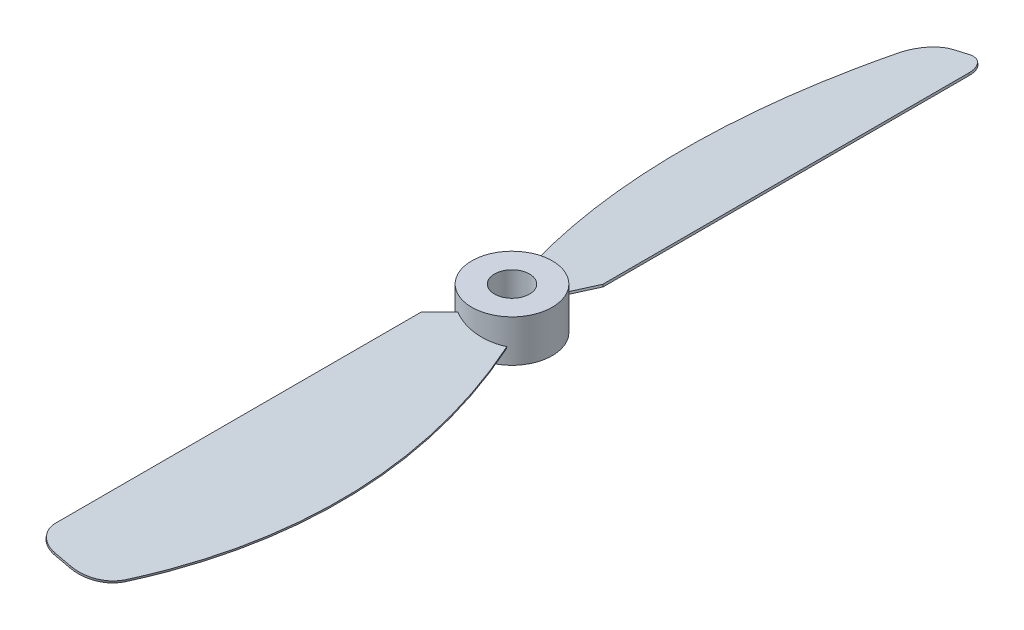
SolidWorks part; units mm, degrees
ref_plane "Front Plane" through (0, 0, 0) normal (0, 0, 1) x (1, 0, 0)
ref_plane "Top Plane" through (0, 0, 0) normal (0, 1, 0) x (1, 0, 0)
ref_plane "Right Plane" through (0, 0, 0) normal (1, 0, 0) x (0, 0, -1)
sketch "Sketch1" plane through (0, 0, 0) normal (0, 1, 0) x (1, 0, 0)
  circle A0 centre (0, 0) radius 5.75
  dimension "D1" = 11.5
extrude "Boss-Extrude1" add sketch "Sketch1" along normal mid plane 6
sketch "Sketch3" plane through (0, 0, 0) normal (0, 0, 1) x (1, 0, 0)
  line L0 (-5.75, 1.3275) -> (5.75, -1.3275) construction
  line L1 (5.75, -3) -> (5.75, 3) construction
  line L2 (-5.75, -3) -> (5.75, -3) construction
  point P6 (0, 0)
  dimension "D1" = 13
ref_plane "Plane1" through (0, 0, 0) normal (-0.225, -0.9744, 0) x (0.9744, -0.225, 0)
sketch "Sketch4" plane through (0, 0, 0) normal (-0.225, -0.9744, 0) x (0.9744, -0.225, 0)
  line L7 (-2.097, 4.1791) -> (-4.9278, 8.202)
  line L8 (-4.9278, 8.202) -> (-4.9278, 60.5)
  line L9 (-1.9278, 63.5) -> (0.3859, 63.5)
  line L10 (3.6481, 63.5) -> (3.6481, 4.1791) construction
  arc A4 (-4.9278, 60.5) -> (-1.9278, 63.5) centre (-1.9278, 60.5) cw
  arc A5 (0.3859, 63.5) -> (5.0995, 60.1679) centre (0.3859, 58.5) cw
  ellipse E2 centre (0.6749, 0) end of major axis (0.6749, 5.75) minor radius 5.6026 construction
  spline S0 degree 3 poles (3.6481, 4.1791) (11.2465, 22.5372) (11.5574, 41.9176) (5.0995, 60.1679) knots 0 0 0 0 0.942592 0.942592 0.942592 0.942592
  spline S1 degree 1 poles (-2.097, 4.1791) (3.6481, 4.1791) knots 0 0 1 1
  point P29 (-5.7556, 63.5)
  dimension "D1" = 63.5
  dimension "D2" = 3
  dimension "D3" = 5
extrude "Boss-Extrude2" add sketch "Sketch4" along normal mid plane 0.3
pattern_circular "CirPattern1" count 2 over 360 about axis through (0, -3, 0) along (0, 1, 0) of "Boss-Extrude2"
sketch "Sketch5" plane through (0, -3, 0) normal (0, -1, 0) x (1, 0, 0)
  circle A0 centre (0, 0) radius 2.5
  dimension "D1" = 5
extrude "Cut-Extrude1" cut sketch "Sketch5" against normal through all
chamfer "Chamfer1" distance 1 angle 45 1 edges at (0, -3, -2.5)
equation "\"q11.5\"=72.2899"
